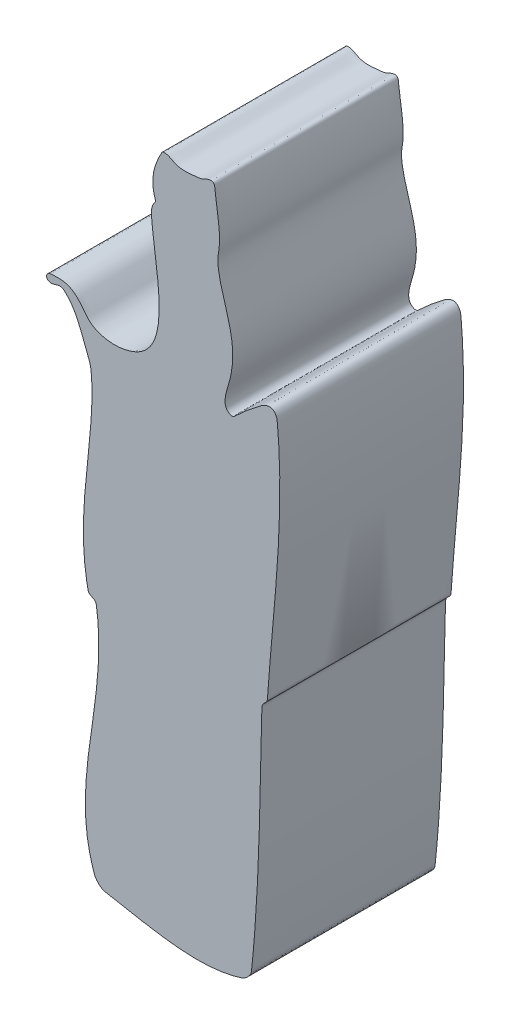
SolidWorks part; units mm, degrees
ref_plane "Front Plane" through (0, 0, 0) normal (0, 0, 1) x (1, 0, 0)
ref_plane "Top Plane" through (0, 0, 0) normal (0, 1, 0) x (1, 0, 0)
ref_plane "Right Plane" through (0, 0, 0) normal (1, 0, 0) x (0, 0, -1)
sketch "CADView Core Profile" plane through (0, 0, 0) normal (0, 0, 1) x (1, 0, 0)
  spline S0 degree 3 poles (-3.7161, 9.0277) (-0.1825, 10.5348) (-1.5562, 15.467) (-1.755, 18.9515) (-1.394, 19.3455) (-1.8295, 20.491) (-1.5177, 21.629) (-0.937, 22.6582) (-0.5334, 22.6981) (0.1451, 22.1555) (1.0941, 22.2825) (1.9298, 22.3619) (2.2772, 22.6117) (2.6337, 22.6223) (2.7739, 22.4689) (2.8868, 21.0777) (3.2829, 19.6535) (2.9629, 17.989) (3.2724, 15.4287) (4.8595, 12.9856) (3.1827, 9.1749) (4.0665, 8.836) (4.7446, 9.5017) (5.4754, 10.0958) (6.3044, 10.7383) (6.7774, 10.8131) (7.0376, 10.6456) (7.1935, 10.362) (7.7732, 4.3852) (6.9246, -1.243) (6.5027, -7.504) (6.1305, -7.695) (5.9737, -13.7443) (5.9621, -18.9737) (5.3704, -24.7251) (5.1444, -25.0203) (4.8601, -25.2552) (1.6159, -26.2899) (-1.8349, -25.4187) (-5.1857, -24.8305) (-5.4735, -24.5986) (-5.7026, -24.3308) (-7.6148, -18.907) (-4.7363, -13.327) (-5.6653, -7.2473) (-6.1599, -7.1872) (-7.0072, -3.0808) (-5.9769, 1.2995) (-5.9069, 5.9383) (-6.0475, 7.0819) (-6.6443, 8.426) (-6.9841, 9.8357) (-8.2328, 10.933) (-8.7875, 10.4842) (-9.1424, 10.7597) (-9.1712, 10.974) (-9.0101, 11.177) (-8.5955, 11.1912) (-8.1078, 11.2288) (-7.4757, 11.0711) (-6.7297, 10.5319) (-6.3018, 9.706) (-4.9407, 8.9652) (-3.7161, 9.0277) (-0.1825, 10.5348) (-1.5562, 15.467) knots -0.025496 -0.021795 -0.000752 0 0.069438 0.078635 0.079785 0.081102 0.105272 0.106414 0.107606 0.114101 0.12568 0.128859 0.133928 0.135512 0.136709 0.13845 0.16801 0.17101 0.178596 0.228062 0.244811 0.245989 0.24891 0.264441 0.270996 0.272959 0.275371 0.277777 0.280454 0.41691 0.419234 0.422535 0.425291 0.554667 0.557458 0.559901 0.563268 0.566086 0.640125 0.643159 0.645628 0.648727 0.651432 0.781071 0.783424 0.787709 0.789886 0.877317 0.895866 0.899912 0.904545 0.930648 0.933946 0.940752 0.942218 0.943715 0.945407 0.947696 0.953068 0.957252 0.962834 0.974504 0.978205 0.999248 1 1.069438 1.078635 1.079785 only from (-2.8433, 9.4006) to (-2.8433, 9.4006)
extrude "CADView Core Extrude" add sketch "CADView Core Profile" along normal blind 13.0313
